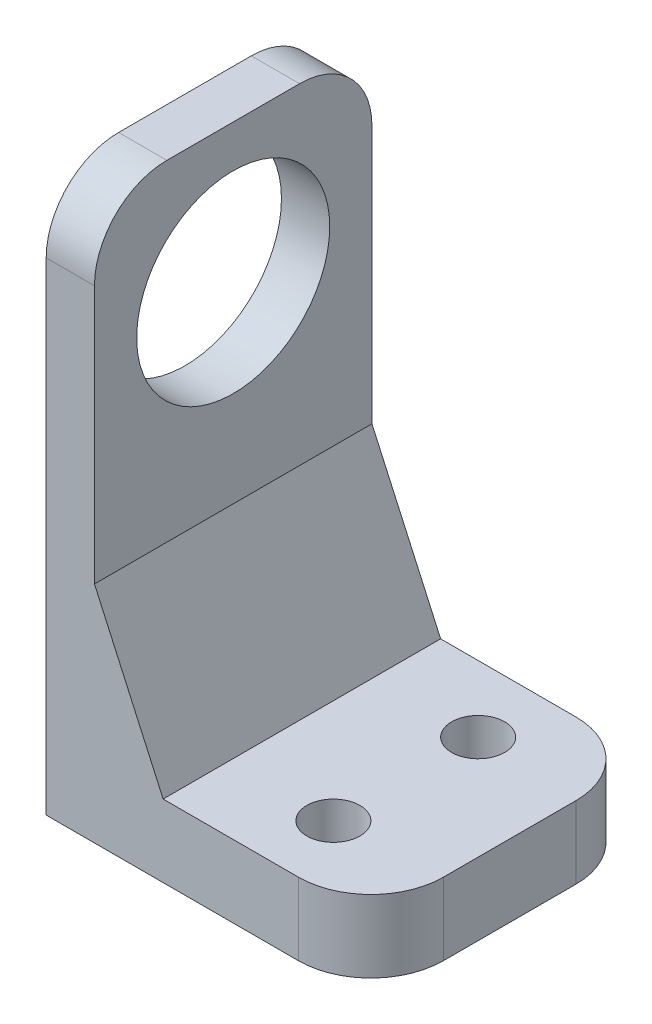
SolidWorks part; units mm, degrees
ref_plane "前视基准面" through (0, 0, 0) normal (0, 0, 1) x (1, 0, 0)
ref_plane "上视基准面" through (0, 0, 0) normal (0, 1, 0) x (1, 0, 0)
ref_plane "右视基准面" through (0, 0, 0) normal (1, 0, 0) x (0, 0, -1)
sketch "草图1" plane through (0, 0, 0) normal (0, 1, 0) x (1, 0, 0)
  line L1 (24.9505, -5.75) -> (-24.9505, -5.75)
  line L2 (24.9505, -5.75) -> (24.9505, 5.75)
  line L3 (24.9505, 5.75) -> (-24.9505, 5.75)
  line L4 (-24.9505, -5.75) -> (-24.9505, 5.75)
  line L5 (24.9505, -5.75) -> (-24.9505, 5.75) construction
  line L6 (24.9505, 5.75) -> (-24.9505, -5.75) construction
  point P0 (0, 0)
extrude "凸台-拉伸1" add sketch "草图1" along normal blind 3
sketch "草图3" plane through (-24.9505, 0, 0) normal (-1, 0, 0) x (0, 0, 1)
  line L1 (-5.75, 0) -> (5.75, 0)
  line L2 (-5.75, 0) -> (-5.75, 23)
  line L3 (-5.75, 23) -> (5.75, 23)
  line L4 (5.75, 0) -> (5.75, 23)
extrude "凸台-拉伸2" add sketch "草图3" against normal blind 2
sketch "草图4" plane through (-22.9505, 0, 0) normal (1, 0, 0) x (0, 0, -1)
  circle A0 centre (0, 17.25) radius 4
extrude "切除-拉伸1" cut sketch "草图4" against normal blind 3
sketch "草图7" plane through (0, 3, 0) normal (0, 1, 0) x (1, 0, 0)
  line L1 (-11.4933, 16.6753) -> (33.0344, 16.6753)
  line L2 (-11.4933, 16.6753) -> (-11.4933, -21.4885)
  line L3 (-11.4933, -21.4885) -> (33.0344, -21.4885)
  line L4 (33.0344, 16.6753) -> (33.0344, -21.4885)
extrude "切除-拉伸2" cut sketch "草图7" against normal blind 10
sketch "草图8" plane through (0, 0, 5.75) normal (0, 0, 1) x (1, 0, 0)
  line L0 (-22.9505, 9.2956) -> (-22.9505, 3)
  line L1 (-22.9505, 3) -> (-22.9505, 23) construction
  line L2 (-22.9505, 3) -> (-20.1039, 3)
  line L3 (-22.9505, 3) -> (-11.4933, 3) construction
  line L4 (-20.1039, 3) -> (-22.9505, 9.2956)
extrude "凸台-拉伸3" add sketch "草图8" against normal blind 11.5
sketch "草图9" plane through (0, 3, 0) normal (0, 1, 0) x (1, 0, 0)
  circle A0 centre (-15.7986, 3) radius 1.1
  circle A1 centre (-15.7986, -3) radius 1.1
extrude "切除-拉伸3" cut sketch "草图9" against normal blind 10
fillet "圆角2" radius 3 2 edges at (-23.9505, 23, -5.75) (-23.9505, 23, 5.75)
fillet "圆角3" radius 3 2 edges at (-11.4933, 1.5, -5.75) (-11.4933, 1.5, 5.75)
